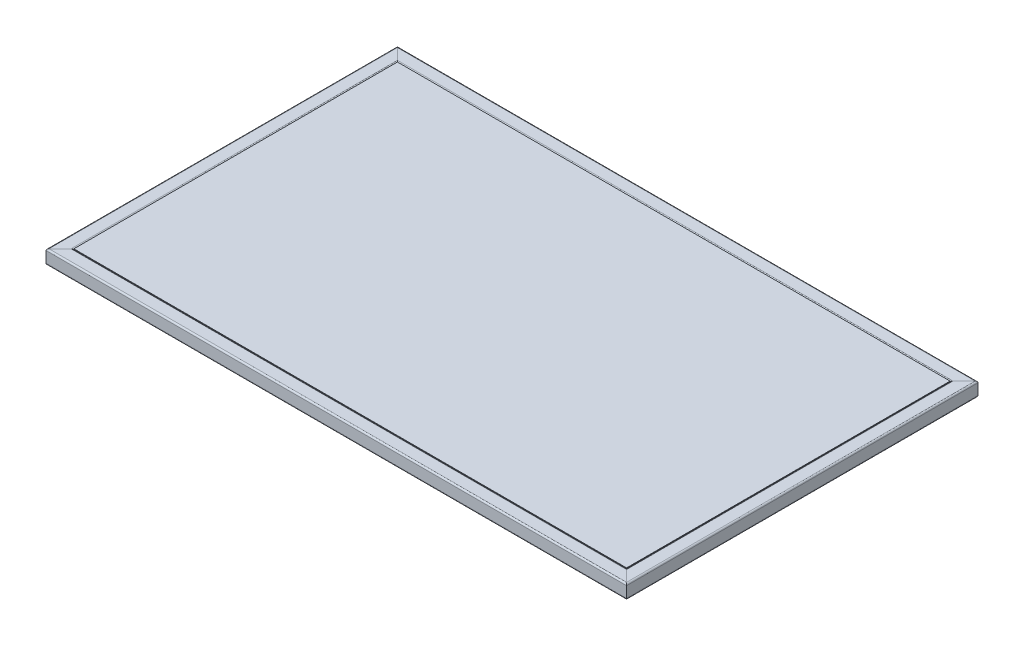
SolidWorks part; units mm, degrees
ref_plane "Alzado" through (0, 0, 0) normal (0, 0, 1) x (1, 0, 0)
ref_plane "Planta" through (0, 0, 0) normal (0, 1, 0) x (1, 0, 0)
ref_plane "Vista lateral" through (0, 0, 0) normal (1, 0, 0) x (0, 0, -1)
sketch "Croquis1" plane through (0, 0, 0) normal (0, 1, 0) x (1, 0, 0)
  line L1 (-396.5, 240) -> (396.5, 240)
  line L2 (-396.5, 240) -> (-396.5, -240)
  line L3 (-396.5, -240) -> (396.5, -240)
  line L4 (396.5, 240) -> (396.5, -240)
  line L5 (-396.5, 240) -> (396.5, -240) construction
  line L6 (-396.5, -240) -> (396.5, 240) construction
  point P0 (0, 0)
  dimension "D1" = 793
  dimension "D2" = 480
other "Tubo cuadrado 2 X 2 X 0.25(1)"
ref_plane "Plano1" through (-386.975, 9.525, -240) normal (0, 0, 1) x (1, 0, 0)
sketch "Sketch1" plane through (-386.975, 9.525, -240) normal (0, 0, 1) x (1, 0, 0)
  line L0 (-7.525, -8.525) -> (7.525, -8.525)
  line L1 (-8.525, -7.525) -> (-8.525, 7.525)
  line L2 (7.525, 8.525) -> (-7.525, 8.525)
  line L3 (8.525, 7.525) -> (8.525, -7.525)
  line L4 (-7.525, -9.525) -> (7.525, -9.525)
  line L5 (-9.525, -7.525) -> (-9.525, 7.525)
  line L6 (7.525, 9.525) -> (-7.525, 9.525)
  line L7 (9.525, 7.525) -> (9.525, -7.525)
  line L8 (0, 0) -> (8.525, 0) construction
  line L9 (0, 0) -> (0, 8.525) construction
  arc A0 (9.525, 7.525) -> (7.525, 9.525) centre (7.525, 7.525) ccw
  arc A1 (7.525, -9.525) -> (9.525, -7.525) centre (7.525, -7.525) ccw
  arc A2 (-9.525, -7.525) -> (-7.525, -9.525) centre (-7.525, -7.525) ccw
  arc A3 (-7.525, 9.525) -> (-9.525, 7.525) centre (-7.525, 7.525) ccw
  arc A4 (-7.525, 8.525) -> (-8.525, 7.525) centre (-7.525, 7.525) ccw
  arc A5 (8.525, 7.525) -> (7.525, 8.525) centre (7.525, 7.525) ccw
  arc A6 (7.525, -8.525) -> (8.525, -7.525) centre (7.525, -7.525) ccw
  arc A7 (-8.525, -7.525) -> (-7.525, -8.525) centre (-7.525, -7.525) ccw
  point P3 (0, 9.525)
  point P4 (9.525, 0)
  point P5 (0, -9.525)
  point P6 (-9.525, 0)
  point P7 (-9.525, 9.525)
  point P8 (-9.525, -9.525)
  point P33 (0, 0)
  point P35 (9.525, -9.525)
  point P36 (9.525, 9.525)
  point P37 (0, 0)
  dimension "D1" = 2
  dimension "Thickness" = 1
  dimension "V_leg" = 19.05
sketch "Croquis2" plane through (0, 19.05, 0) normal (0, 1, 0) x (1, 0, 0)
  line L1 (-377.45, -220.95) -> (377.45, -220.95)
  line L2 (-377.45, -220.95) -> (-377.45, 220.95)
  line L3 (-377.45, 220.95) -> (377.45, 220.95)
  line L4 (377.45, -220.95) -> (377.45, 220.95)
  line L5 (-377.45, -220.95) -> (377.45, 220.95) construction
  line L6 (-377.45, 220.95) -> (377.45, -220.95) construction
  point P0 (0, 0)
extrude "Saliente-Extruir1" add sketch "Croquis2" against normal blind 12.7 separate body
shell "Vaciado1" thickness 1.9
